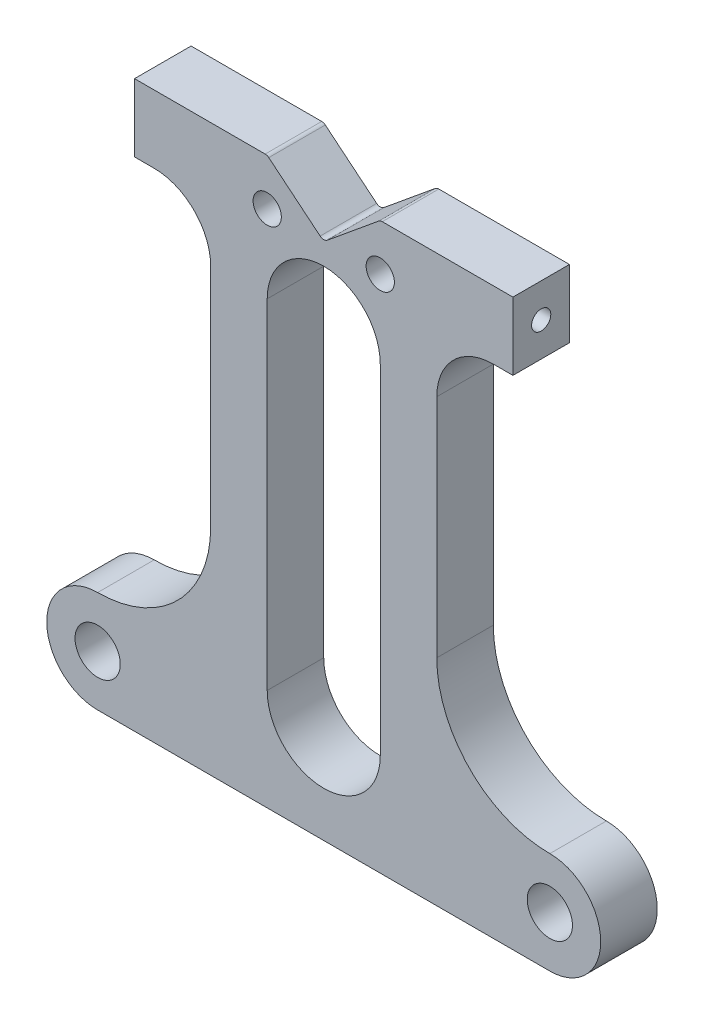
SolidWorks part; units mm, degrees
ref_plane "Front Plane" through (0, 0, 0) normal (0, 0, 1) x (1, 0, 0)
ref_plane "Top Plane" through (0, 0, 0) normal (0, 1, 0) x (1, 0, 0)
ref_plane "Right Plane" through (0, 0, 0) normal (1, 0, 0) x (0, 0, -1)
sketch "Sketch1" plane through (0, 0, 0) normal (0, 0, 1) x (1, 0, 0)
  line L0 (0, 0) -> (40, 0)
  line L5 (0, 0) -> (0, 28.65) construction
  line L6 (40, -9) -> (0, -9)
  line L7 (0, -9) -> (0, 91)
  line L8 (0, 82.7763) -> (10, 91)
  line L9 (10, 91) -> (33.47, 91)
  line L10 (33.47, 91) -> (33.47, 79)
  line L11 (33.47, 79) -> (30, 79)
  line L12 (0, 69) -> (0, 9) construction
  line L13 (20, 69) -> (20, 29)
  line L14 (10, 69) -> (10, 9)
  line L15 (-10, 69) -> (-10, 9)
  circle A0 centre (40, 0) radius 4
  circle A1 centre (40, 0) radius 9
  circle A2 centre (10, 82.7763) radius 2.5
  arc A3 (20, 69) -> (30, 79) centre (30, 69) cw
  arc A4 (20, 29) -> (40, 9) centre (40, 29) ccw
  arc A5 (10, 69) -> (-10, 69) centre (0, 69) ccw
  arc A6 (-10, 9) -> (10, 9) centre (0, 9) ccw
  point P25 (0, 39)
  dimension "D2" = 8
  dimension "D6" = 5
  dimension "D11" = 10
  dimension "D1" = 40
  dimension "D4" = 100
  dimension "D5" = 50.567
  dimension "D7" = 10
  dimension "D8" = 33.47
  dimension "D9" = 12
  dimension "D10" = 20
  dimension "D12" = 20
  dimension "D3" = 5
extrude "Boss-Extrude1" add sketch "Sketch1" along normal mid plane 10
mirror "Mirror1" about plane through (0, 0, 5) normal (-1, 0, 0) of "Boss-Extrude1"
fillet "Fillet1" radius 1 3 edges at (-10, 91, 0) (10, 91, 0) (0, 82.7763, 0)
sketch "Sketch4" plane through (33.47, 0, 0) normal (1, 0, 0) x (0, 0, -1)
  line L0 (0, 85) -> (-5, 91) construction
  line L2 (0, 85) -> (5, 79) construction
  point P0 (0, 85)
hole_wizard "M3 Clearance Hole1" positions "Sketch4" profile "Sketch3" hole size "M3" standard "ANSI Metric"
sketch "Sketch3" plane through (33.47, 85, 0) normal (0, 1, 0) x (0, 0, -1)
  line L0 (0, 0) -> (0, 6.0215)
  line L1 (0, 6.0215) -> (1.7, 5)
  line L2 (1.7, 5) -> (1.7, 0)
  line L5 (1.7, 0) -> (0, 0)
  line L10 (0, 6.0215) -> (-1.7, 5) construction
  line L11 (0, -6.35) -> (0, 107.95) construction
  dimension "Hole Dia." = 3.4
  dimension "Hole Depth" = 5
  dimension "Drill Angle" = 118
